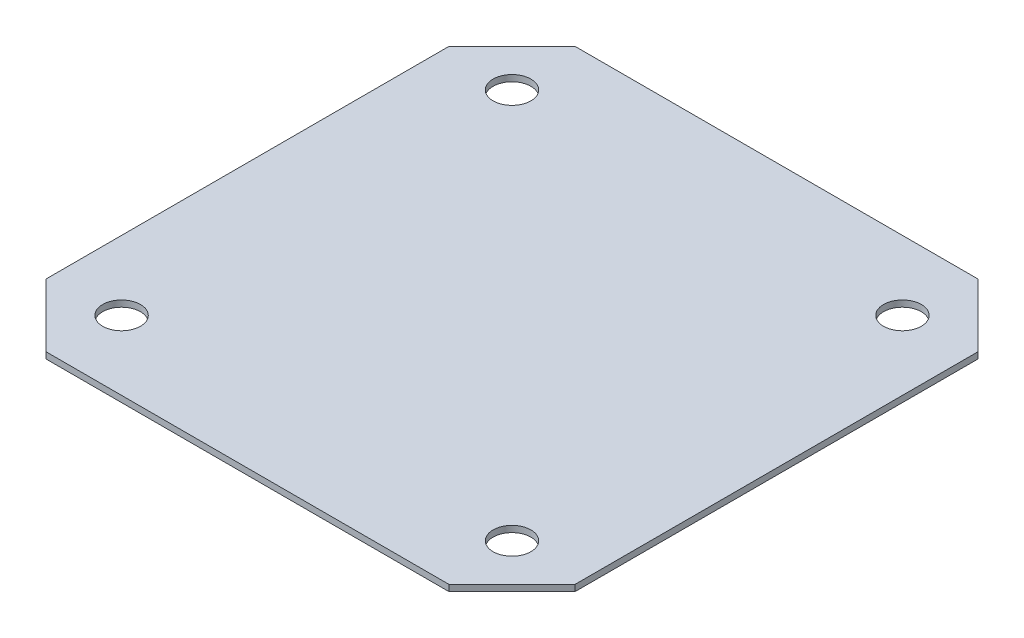
SolidWorks part; units mm, degrees
ref_plane "Alzado" through (0, 0, 0) normal (0, 0, 1) x (1, 0, 0)
ref_plane "Planta" through (0, 0, 0) normal (0, 1, 0) x (1, 0, 0)
ref_plane "Vista lateral" through (0, 0, 0) normal (1, 0, 0) x (0, 0, -1)
sketch "Croquis1" plane through (0, 0, 0) normal (0, 1, 0) x (1, 0, 0)
  line L1 (0, 0) -> (42, 0)
  line L2 (0, 0) -> (0, -42)
  line L3 (0, -42) -> (42, -42)
  line L4 (42, 0) -> (42, -42)
  dimension "D1" = 42
  dimension "D2" = 42
extrude "Saliente-Extruir1" add sketch "Croquis1" along normal blind 0.5
sketch "Croquis2" plane through (0, 0.5, 0) normal (0, 1, 0) x (1, 0, 0)
  line L0 (0, 0) -> (42, -42) construction
  line L2 (5.5, -36.5) -> (36.5, -36.5)
  line L3 (5.5, -36.5) -> (5.5, -5.5)
  line L4 (5.5, -5.5) -> (36.5, -5.5)
  line L5 (36.5, -36.5) -> (36.5, -5.5)
  line L6 (5.5, -36.5) -> (36.5, -5.5) construction
  line L7 (5.5, -5.5) -> (36.5, -36.5) construction
  circle A0 centre (5.5, -5.5) radius 1.5
  circle A1 centre (36.5, -5.5) radius 1.5
  circle A2 centre (36.5, -36.5) radius 1.5
  circle A3 centre (5.5, -36.5) radius 1.5
  point P4 (21, -21)
  point P14 (5.4292, -5.4292)
  dimension "D2" = 3
  dimension "D1" = 31
extrude "Cortar-Extruir1" cut sketch "Croquis2" against normal blind 0.5 contours A1 | A0 | A2 | A3
chamfer "Chaflán1" distance 5 angle 45 4 edges at (0, 0.25, 42) (42, 0.25, 42) (42, 0.25, 0) (0, 0.25, 0)
